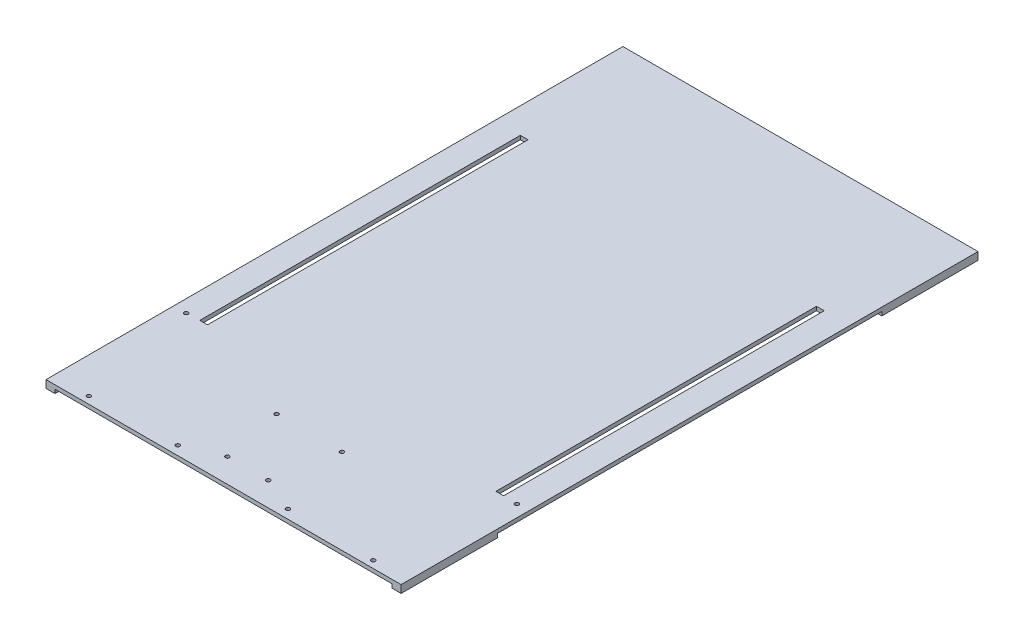
SolidWorks part; units mm, degrees
ref_plane "Front Plane" through (0, 0, 0) normal (0, 0, 1) x (1, 0, 0)
ref_plane "Top Plane" through (0, 0, 0) normal (0, 1, 0) x (1, 0, 0)
ref_plane "Right Plane" through (0, 0, 0) normal (1, 0, 0) x (0, 0, -1)
sketch "Sketch1" plane through (0, 0, 0) normal (0, 0, 1) x (1, 0, 0)
  line L1 (19.86, -14.9279) -> (-257.14, -14.9279)
  line L2 (19.86, -14.9279) -> (19.86, -11.9279)
  line L3 (19.86, -11.9279) -> (-257.14, -11.9279)
  line L4 (-257.14, -14.9279) -> (-257.14, -11.9279)
  line L5 (19.86, -14.9279) -> (-257.14, -11.9279) construction
  line L6 (19.86, -11.9279) -> (-257.14, -14.9279) construction
  point P0 (-118.64, -13.4279)
extrude "Boss-Extrude1" add sketch "Sketch1" along normal blind 450
sketch "Sketch2" plane through (0, -11.9279, 0) normal (0, 1, 0) x (1, 0, 0)
  line L0 (19.86, -450) -> (-257.14, -450) construction
  line L1 (-237.14, -100) -> (-231.14, -100)
  line L2 (-237.14, -100) -> (-237.14, -350)
  line L3 (-237.14, -350) -> (-231.14, -350)
  line L4 (-231.14, -100) -> (-231.14, -350)
  line L5 (-6.14, -100) -> (-0.14, -100)
  line L6 (-6.14, -100) -> (-6.14, -350)
  line L7 (-6.14, -350) -> (-0.14, -350)
  line L8 (-0.14, -100) -> (-0.14, -350)
  line L9 (19.86, 0) -> (-257.14, 0) construction
  line L10 (-257.14, -450) -> (-257.14, 0) construction
  line L11 (19.86, -450) -> (19.86, 0) construction
  dimension "D1" = 100
  dimension "D2" = 100
  dimension "D3" = 100
  dimension "D4" = 100
  dimension "D5" = 20
  dimension "D6" = 20
  dimension "D7" = 6
  dimension "D8" = 6
extrude "Cut-Extrude1" cut sketch "Sketch2" against normal up to next
sketch "Sketch3" plane through (0, -11.9279, 0) normal (0, 1, 0) x (1, 0, 0)
  circle A0 centre (-102.46, -431.323) radius 1.55
  circle A1 centre (-75.46, -442.9832) radius 1.55
  circle A2 centre (-92.91, -383.4048) radius 1.55
  circle A3 centre (10.54, -350.4048) radius 1.55
  circle A4 centre (-7.46, -444.4332) radius 1.55
  circle A5 centre (-247.34, -350.4056) radius 1.55
  circle A6 centre (-229.34, -444.434) radius 1.55
  circle A7 centre (-161.34, -442.984) radius 1.55
  circle A8 centre (-134.34, -431.3238) radius 1.55
  circle A9 centre (-143.89, -383.4056) radius 1.55
extrude "Cut-Extrude2" cut sketch "Sketch3" against normal up to next
sketch "Sketch4" plane through (0, -14.9279, 0) normal (0, -1, 0) x (1, 0, 0)
  line L0 (1.65, 0) -> (-1.65, 0) construction
  line L1 (-257.14, 450) -> (-250.14, 450)
  line L2 (-257.14, 450) -> (-257.14, 375)
  line L3 (-257.14, 375) -> (-250.14, 375)
  line L4 (-250.14, 450) -> (-250.14, 375)
  line L5 (19.86, 450) -> (12.86, 450)
  line L6 (19.86, 450) -> (19.86, 375)
  line L7 (19.86, 375) -> (12.86, 375)
  line L8 (12.86, 450) -> (12.86, 375)
  line L9 (-257.14, 0) -> (-250.14, 0)
  line L10 (-257.14, 0) -> (-257.14, 75)
  line L11 (-257.14, 75) -> (-250.14, 75)
  line L12 (-250.14, 0) -> (-250.14, 75)
  line L13 (19.86, 450) -> (19.86, 0) construction
  line L14 (19.86, 0) -> (12.86, 0)
  line L15 (19.86, 0) -> (19.86, 75)
  line L16 (19.86, 75) -> (12.86, 75)
  line L17 (12.86, 0) -> (12.86, 75)
  line L18 (-257.14, 0) -> (19.86, 0) construction
  line L19 (-118.64, 0) -> (-118.64, 217.4779) construction
  line L20 (-121.14, 199.9779) -> (-116.14, 199.9779)
  line L21 (-121.14, 199.9779) -> (-121.14, 234.9779)
  line L22 (-121.14, 234.9779) -> (-116.14, 234.9779)
  line L23 (-116.14, 199.9779) -> (-116.14, 234.9779)
  line L24 (-121.14, 199.9779) -> (-116.14, 234.9779) construction
  line L25 (-121.14, 234.9779) -> (-116.14, 199.9779) construction
  point P22 (-118.64, 217.4779)
  dimension "D1" = 75
  dimension "D2" = 7
  dimension "D3" = 75
  dimension "D4" = 75
  dimension "D5" = 7
  dimension "D6" = 5
  dimension "D7" = 35
extrude "Boss-Extrude2" add sketch "Sketch4" along normal blind 3
